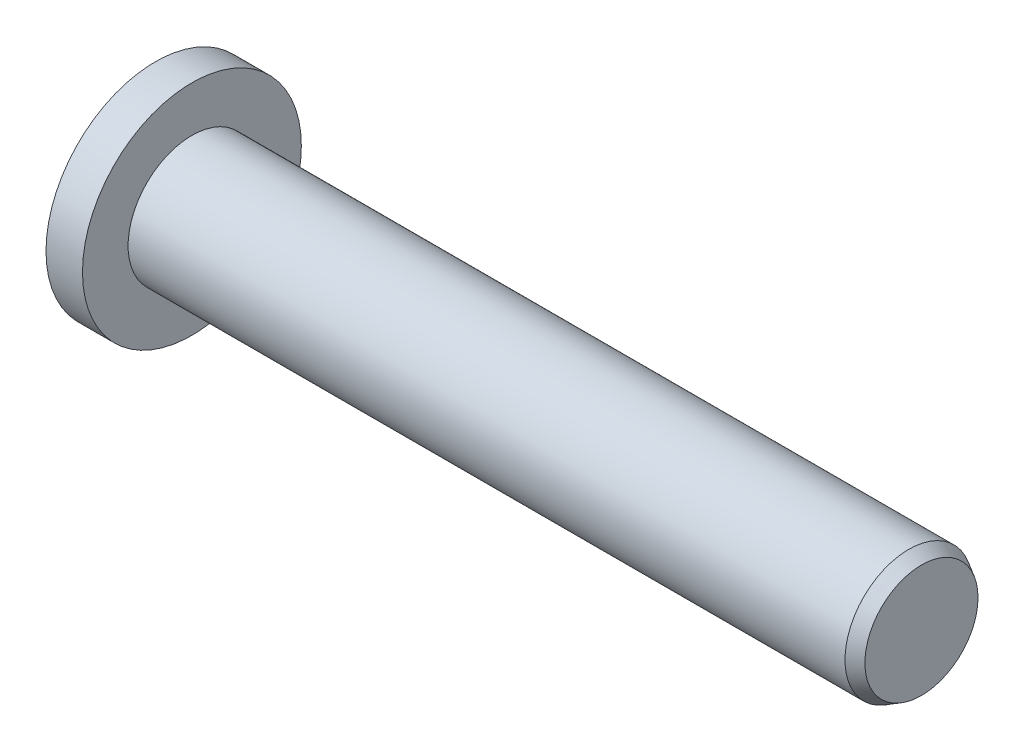
SolidWorks part; units mm, degrees
ref_plane "Спереди" through (0, 0, 0) normal (0, 0, 1) x (1, 0, 0)
ref_plane "Сверху" through (0, 0, 0) normal (0, 1, 0) x (1, 0, 0)
ref_plane "Справа" through (0, 0, 0) normal (1, 0, 0) x (0, 0, -1)
sketch "Эскиз1" plane through (0, 0, 0) normal (0, 0, 1) x (1, 0, 0)
  line L0 (0, 0) -> (-1.9733, 0) construction
  line L1 (0, 0) -> (0, 3)
  line L2 (0, 3) -> (1, 3)
  line L3 (1, 3) -> (1, 1.75)
  line L4 (1, 1.75) -> (20.6536, 1.75)
  line L5 (21, 1.55) -> (21, 0)
  line L6 (21, 0) -> (0, 0)
  line L7 (20.6536, 1.75) -> (21, 1.55)
  point P7 (21, 1.75)
  dimension "D1" = 1
  dimension "D2" = 21
  dimension "D3" = 3.5
  dimension "D4" = 6
  dimension "D5" = 0.2
  dimension "D6" = 60
revolve "Повернуть1" add sketch "Эскиз1" angle 360 about L0
